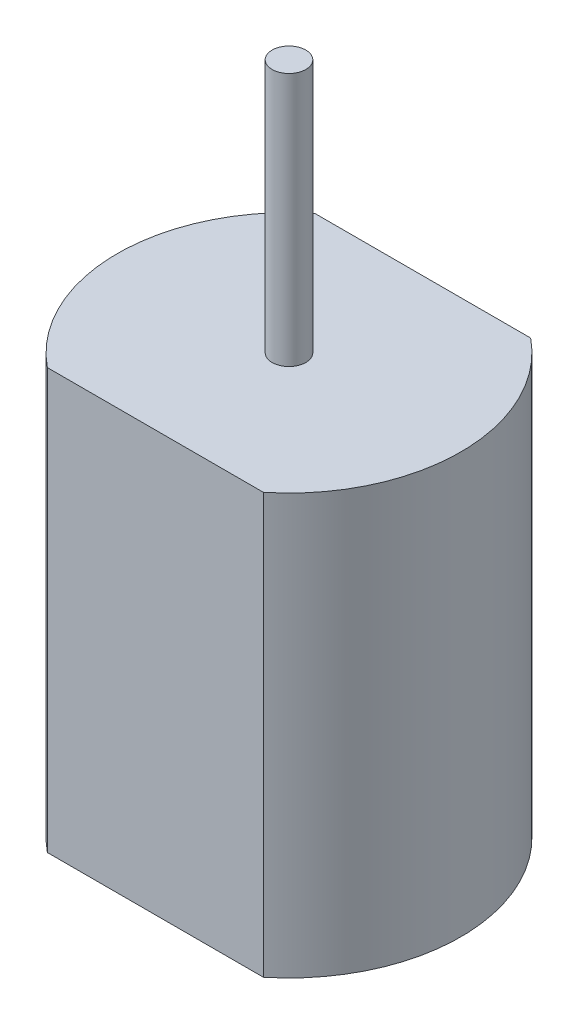
SolidWorks part; units mm, degrees
ref_plane "前视基准面" through (0, 0, 0) normal (0, 0, 1) x (1, 0, 0)
ref_plane "上视基准面" through (0, 0, 0) normal (0, 1, 0) x (1, 0, 0)
ref_plane "右视基准面" through (0, 0, 0) normal (1, 0, 0) x (0, 0, -1)
other "Configuration Table"
sketch "草图1" plane through (0, 0, 0) normal (0, 1, 0) x (1, 0, 0)
  line L1 (4.8083, 5.95) -> (-4.8083, 5.95)
  line L3 (4.8083, -5.95) -> (-4.8083, -5.95)
  arc A0 (-4.8083, 5.95) -> (-4.8083, -5.95) centre (0, 0) ccw
  circle A1 centre (0, 0) radius 5.95 construction
  arc A2 (4.8083, -5.95) -> (4.8083, 5.95) centre (0, 0) ccw
  dimension "D1" = 15.3
  dimension "D2" = 11.9
extrude "凸台-拉伸1" add sketch "草图1" along normal blind 18.7
sketch "草图2" plane through (0, 18.7, 0) normal (0, 1, 0) x (1, 0, 0)
  circle A0 centre (0, 0) radius 0.75
  dimension "D1" = 1.5
extrude "凸台-拉伸2" add sketch "草图2" along normal blind 11.3
